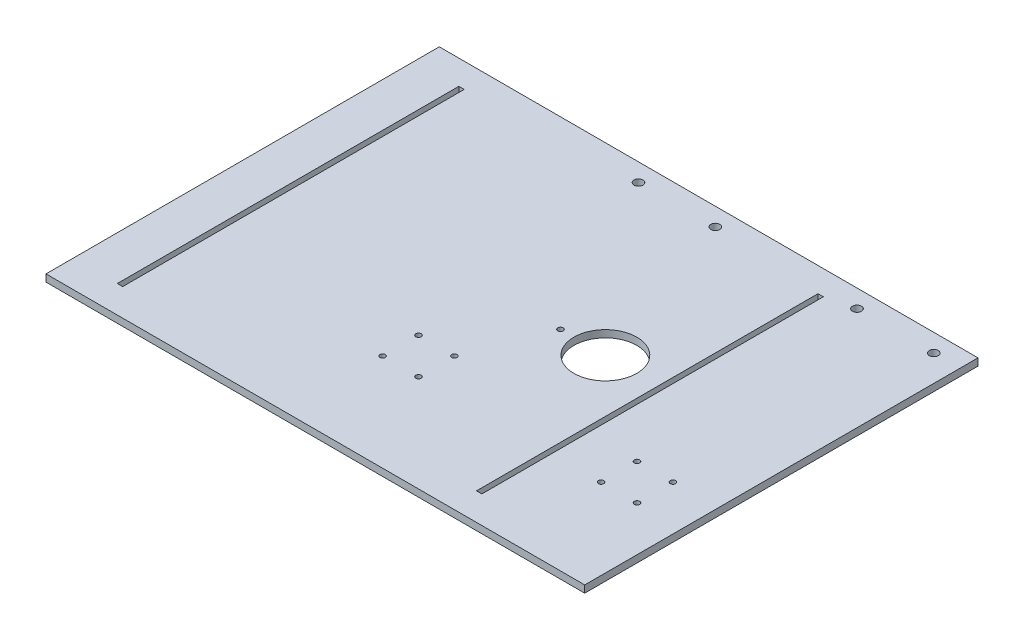
SolidWorks part; units mm, degrees
ref_plane "Front Plane" through (0, 0, 0) normal (0, 0, 1) x (1, 0, 0)
ref_plane "Top Plane" through (0, 0, 0) normal (0, 1, 0) x (1, 0, 0)
ref_plane "Right Plane" through (0, 0, 0) normal (1, 0, 0) x (0, 0, -1)
sketch "Sketch1" plane through (0, 0, 0) normal (0, 1, 0) x (1, 0, 0)
  line L0 (-125.5, 95.8859) -> (-125.5, -94.2851)
  line L1 (-150, -109.5) -> (150, -109.5)
  line L2 (-150, -109.5) -> (-150, 109.5)
  line L3 (-150, 109.5) -> (150, 109.5)
  line L4 (150, -109.5) -> (150, 109.5)
  line L5 (-150, -109.5) -> (150, 109.5) construction
  line L6 (-150, 109.5) -> (150, -109.5) construction
  line L7 (-125.5, -94.2851) -> (-122.5, -94.2851)
  line L8 (-122.5, -94.2851) -> (-122.5, 95.8859)
  line L9 (-122.5, 95.8859) -> (-125.5, 95.8859)
  line L10 (74.5, 95.8859) -> (74.5, -94.2851)
  line L11 (74.5, -94.2851) -> (77.5, -94.2851)
  line L12 (77.5, -94.2851) -> (77.5, 95.8859)
  line L13 (77.5, 95.8859) -> (74.5, 95.8859)
  point P0 (0, 0)
  dimension "D1" = 219
  dimension "D2" = 300
  dimension "D3" = 3
  dimension "D4" = 3
  dimension "D5" = 72.5
  dimension "D6" = 24.5
extrude "Boss-Extrude1" add sketch "Sketch1" along normal blind 4
sketch "Sketch2" plane through (0, 0, 0) normal (0, -1, 0) x (-1, 0, 0)
  line L0 (150, -109.5) -> (-150, -109.5) construction
  line L1 (-150, -109.5) -> (-150, 109.5) construction
  circle A0 centre (-45, 7) radius 17.5
  dimension "D3" = 35
  dimension "D1" = 116.5
  dimension "D2" = 105
extrude "Cut-Extrude2" cut sketch "Sketch2" against normal through all
sketch "Sketch3" plane through (0, 0, 0) normal (0, -1, 0) x (-1, 0, 0)
  line L0 (-150, -109.5) -> (-150, 109.5) construction
  line L1 (150, -109.5) -> (-150, -109.5) construction
  circle A0 centre (-125, -55.39) radius 1.5
  circle A1 centre (-125, -35.39) radius 1.5
  circle A2 centre (-105, -35.39) radius 1.5
  circle A3 centre (-105, -55.39) radius 1.5
  dimension "D1" = 3
  dimension "D6" = 20
  dimension "D9" = 20
  dimension "D2" = 25
  dimension "D3" = 25
  dimension "D4" = 54.11
  dimension "D5" = 54.11
  dimension "D7" = 20
  dimension "D8" = 20
extrude "Cut-Extrude3" cut sketch "Sketch3" against normal through all both and the other way through all
sketch "Sketch4" plane through (0, 0, 0) normal (0, -1, 0) x (-1, 0, 0)
  line L0 (-150, -109.5) -> (-150, 109.5) construction
  line L1 (150, -109.5) -> (-150, -109.5) construction
  circle A0 centre (-3.32, -55.39) radius 1.5
  circle A1 centre (-3.32, -35.39) radius 1.5
  circle A2 centre (16.68, -35.39) radius 1.5
  circle A3 centre (16.68, -55.39) radius 1.5
  dimension "D1" = 3
  dimension "D2" = 146.68
  dimension "D4" = 146.68
  dimension "D5" = 20
  dimension "D6" = 54.11
  dimension "D7" = 54.11
  dimension "D8" = 20
  dimension "D3" = 20
extrude "Cut-Extrude4" cut sketch "Sketch4" against normal through all both and the other way through all
sketch "Sketch5" plane through (0, 0, 0) normal (0, -1, 0) x (-1, 0, 0)
  line L0 (-150, 109.5) -> (150, 109.5) construction
  line L1 (-150, -109.5) -> (-150, 109.5) construction
  circle A0 centre (-135.39, 99.5) radius 2.5
  circle A1 centre (-92.61, 99.5) radius 2.5
  dimension "D1" = 5
  dimension "D2" = 10
  dimension "D3" = 10
  dimension "D4" = 42.78
  dimension "D5" = 14.61
extrude "Cut-Extrude5" cut sketch "Sketch5" against normal through all both and the other way through all
sketch "Sketch6" plane through (0, 0, 0) normal (0, -1, 0) x (1, 0, 0)
  line L0 (150, -109.5) -> (-150, -109.5) construction
  line L1 (150, 109.5) -> (150, -109.5) construction
  circle A0 centre (13.71, -99.5) radius 2.5
  circle A1 centre (-29.07, -99.5) radius 2.5
  dimension "D1" = 10
  dimension "D2" = 10
  dimension "D3" = 5
  dimension "D4" = 136.29
  dimension "D5" = 42.78
extrude "Cut-Extrude6" cut sketch "Sketch6" against normal through all both and the other way through all
sketch "Sketch7" plane through (0, 4, 0) normal (0, 1, 0) x (1, 0, 0)
  line L0 (150, -109.5) -> (150, 109.5) construction
  line L1 (-150, -109.5) -> (150, -109.5) construction
  circle A0 centre (20, 7) radius 1.5
  dimension "D1" = 3
  dimension "D2" = 130
  dimension "D3" = 116.5
extrude "Cut-Extrude7" cut sketch "Sketch7" against normal through all both and the other way through all
